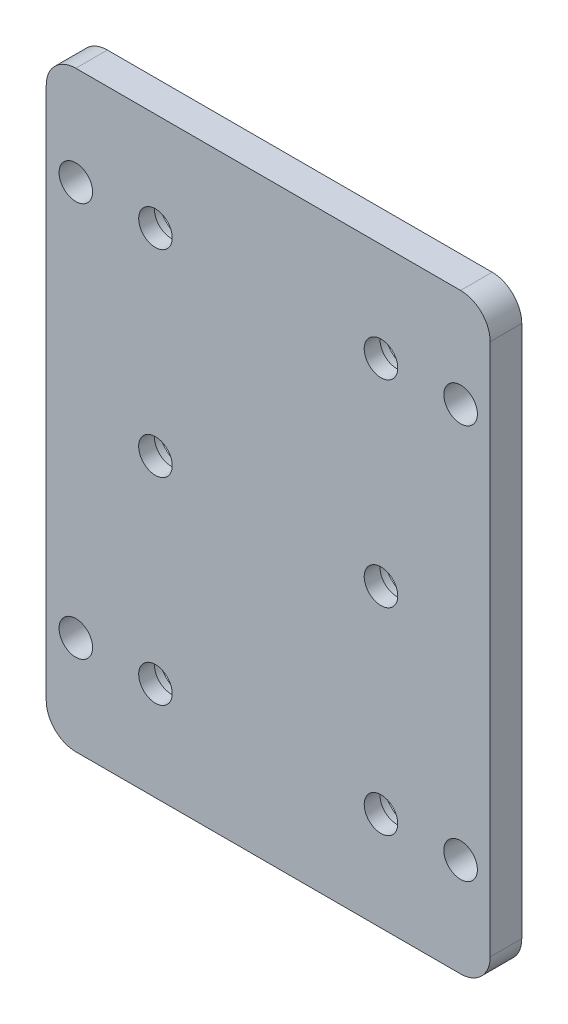
SolidWorks part; units mm, degrees
ref_plane "前基準面" through (0, 0, 0) normal (0, 0, 1) x (1, 0, 0)
ref_plane "上基準面" through (0, 0, 0) normal (0, 1, 0) x (1, 0, 0)
ref_plane "右基準面" through (0, 0, 0) normal (1, 0, 0) x (0, 0, -1)
sketch "草圖1" plane through (0, 0, 0) normal (0, 0, 1) x (1, 0, 0)
  line L1 (-22.5, 30) -> (22.5, 30)
  line L2 (-22.5, 30) -> (-22.5, -30)
  line L3 (-22.5, -30) -> (22.5, -30)
  line L4 (22.5, 30) -> (22.5, -30)
  point P4 (0, 30)
  point P6 (22.5, 0)
  dimension "D1" = 60
  dimension "D2" = 45
extrude "填料-伸長1" add sketch "草圖1" along normal blind 3.2
sketch "草圖3" plane through (0, 0, 3.2) normal (0, 0, 1) x (1, 0, 0)
  line L0 (-15.5, 13.65) -> (15.5, 13.65) construction
  line L1 (-15.5, 6.35) -> (15.5, 6.35) construction
  line L2 (-15.5, 6.35) -> (-15.5, -6.35) construction
  line L3 (-15.5, -6.35) -> (15.5, -6.35) construction
  line L4 (15.5, 6.35) -> (15.5, -6.35) construction
  line L5 (15.5, 26.35) -> (15.5, 13.65) construction
  line L6 (-15.5, 26.35) -> (-15.5, 13.65) construction
  line L7 (-15.5, 26.35) -> (15.5, 26.35) construction
  line L8 (-22.5, 0) -> (22.5, 0) construction
  line L9 (-22.5, 30) -> (-22.5, -30) construction
  line L10 (22.5, -30) -> (22.5, 30) construction
  line L11 (-15.5, -26.35) -> (15.5, -26.35) construction
  line L12 (-15.5, -26.35) -> (-15.5, -13.65) construction
  line L13 (15.5, -26.35) -> (15.5, -13.65) construction
  line L14 (-15.5, -13.65) -> (15.5, -13.65) construction
  circle A0 centre (-11.43, 0) radius 1.7
  circle A1 centre (11.43, 0) radius 1.7
  circle A2 centre (11.43, 20) radius 1.7
  circle A3 centre (-11.43, 20) radius 1.7
  circle A4 centre (-11.43, -20) radius 1.7
  circle A5 centre (11.43, -20) radius 1.7
  point P4 (-15.5, 0)
  point P6 (0, 6.35)
  dimension "D6" = 3.4
  dimension "D7" = 3.4
  dimension "D1" = 31
  dimension "D2" = 12.7
  dimension "D3" = 22.86
  dimension "D4" = 11.43
  dimension "D5" = 2
extrude "除料-伸長2" cut sketch "草圖3" against normal through all
sketch "草圖2" plane through (0, 0, 3.2) normal (0, 0, 1) x (1, 0, 0)
  line L0 (22.5, 30) -> (-22.5, 30) construction
  line L1 (-22.5, 30) -> (-22.5, -30) construction
  line L2 (22.5, -30) -> (22.5, 30) construction
  line L3 (-22.5, 0) -> (22.5, 0) construction
  circle A0 centre (-19.5, 20) radius 1.7
  circle A1 centre (19.5, 20) radius 1.7
  circle A2 centre (19.5, -20) radius 1.7
  circle A3 centre (-19.5, -20) radius 1.7
  circle A4 centre (-19.5, 20) radius 3 construction
  dimension "D5" = 3.4
  dimension "D6" = 3.4
  dimension "D7" = 6
  dimension "D1" = 10
  dimension "D2" = 10
  dimension "D3" = 3
  dimension "D4" = 3
extrude "除料-伸長1" cut sketch "草圖2" against normal through all
fillet "圓角1" radius 3 4 edges at (-22.5, 30, 1.6) (22.5, 30, 1.6) (22.5, -30, 1.6) (-22.5, -30, 1.6)
sketch "草圖4" plane through (0, 0, 0) normal (0, 0, -1) x (-1, 0, 0)
  circle A0 centre (-11.43, 20) radius 3
  circle A1 centre (11.43, 20) radius 3
  circle A2 centre (-11.43, 0) radius 3
  circle A3 centre (11.43, 0) radius 3
  circle A4 centre (-11.43, -20) radius 3
  circle A5 centre (11.43, -20) radius 3
  dimension "D1" = 6
  dimension "D2" = 6
  dimension "D3" = 6
  dimension "D4" = 6
  dimension "D5" = 6
  dimension "D6" = 6
extrude "除料-伸長3" cut sketch "草圖4" against normal blind 1.6
